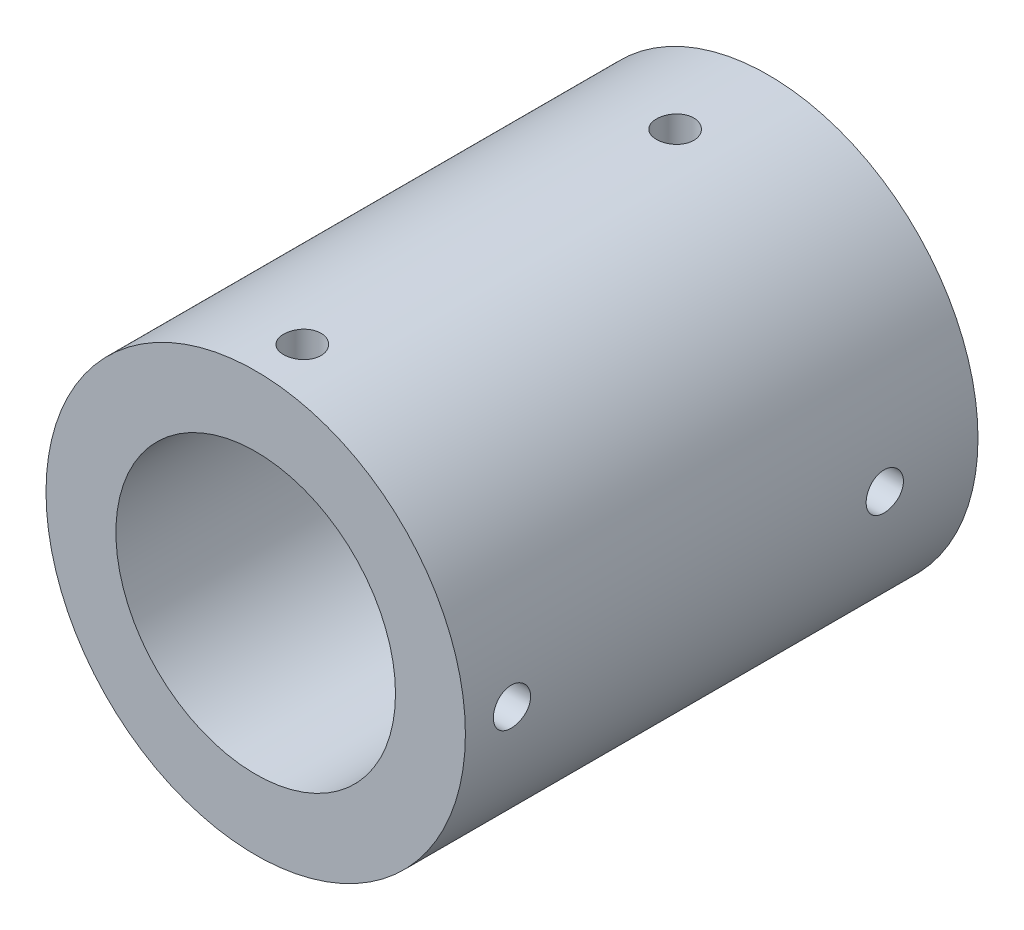
SolidWorks part; units mm, degrees
material "2.0367 (CuZn40)"
ref_plane "Vorne" through (0, 0, 0) normal (0, 0, 1) x (1, 0, 0)
ref_plane "Oben" through (0, 0, 0) normal (0, 1, 0) x (1, 0, 0)
ref_plane "Rechts" through (0, 0, 0) normal (1, 0, 0) x (0, 0, -1)
sketch "Skizze1" plane through (0, 0, 0) normal (0, 0, 1) x (1, 0, 0)
  circle A0 centre (0, 0) radius 9
  dimension "D1" = 18
extrude "Aufsatz-Linear austragen1" add sketch "Skizze1" along normal blind 22
sketch "Skizze2" plane through (0, 0, 22) normal (0, 0, 1) x (1, 0, 0)
  circle A0 centre (0, 0) radius 6
  dimension "D1" = 12
extrude "Schnitt-Linear austragen1" cut sketch "Skizze2" against normal through all
ref_plane "Ebene1" through (9, 0, 0) normal (1, 0, 0) x (0, 0, -1)
ref_plane "Ebene2" through (0, 9, 0) normal (0, 1, 0) x (1, 0, 0)
hole_wizard "M2 Gewindebohrung1" positions "Skizze3" profile "Skizze4" tap size "M2" standard "DIN"
sketch "Skizze3" plane through (9, 0, 0) normal (1, 0, 0) x (0, 0, -1)
  line L0 (9.9, 0) -> (-9.9, 0) construction
  line L1 (0, 9.9) -> (0, -9.9) construction
  point P0 (-4, 0)
  dimension "D1" = 4
cosmetic thread "Bohrungsgewinde1" parameters "D1"=3.0536, "D2"=2
sketch "Skizze4" plane through (9, 0, 4) normal (0, 1, 0) x (0, 0, -1)
  line L0 (0, 0) -> (0, 6.4807)
  line L1 (0, 6.4807) -> (0.8, 6)
  line L2 (0.8, 6) -> (0.8, 0)
  line L5 (0.8, 0) -> (0, 0)
  line L10 (0, 6.4807) -> (-0.8, 6) construction
  line L11 (0, -6.35) -> (0, 107.95) construction
  dimension "Bohrerdurchmesser" = 1.6
  dimension "Bohrungstiefe" = 6
  dimension "Spitzenwinkel" = 118
hole_wizard "M2 Gewindebohrung2" positions "Skizze5" profile "Skizze6" tap size "M2" standard "DIN"
sketch "Skizze5" plane through (0, 9, 0) normal (0, 1, 0) x (1, 0, 0)
  line L0 (0, -9.9) -> (0, 9.9) construction
  line L1 (-9.9, 0) -> (9.9, 0) construction
  point P0 (0, -4)
  dimension "D1" = 4
sketch "Skizze6" plane through (0, 9, 4) normal (1, 0, 0) x (0, 0, 1)
  line L0 (0, 0) -> (0, 6.4807)
  line L1 (0, 6.4807) -> (0.8, 6)
  line L2 (0.8, 6) -> (0.8, 0)
  line L5 (0.8, 0) -> (0, 0)
  line L10 (0, 6.4807) -> (-0.8, 6) construction
  line L11 (0, -6.35) -> (0, 107.95) construction
  dimension "Bohrerdurchmesser" = 1.6
  dimension "Bohrungstiefe" = 6
  dimension "Spitzenwinkel" = 118
cosmetic thread "Bohrungsgewinde2" parameters "D1"=3.0536, "D2"=2
pattern_linear "Lineares Muster1" count 2 spacing 16 along (0, 0, 1) of "M2 Gewindebohrung1"
pattern_linear "Lineares Muster2" count 2 spacing 16 along (0, 0, 1) of "M2 Gewindebohrung2"
